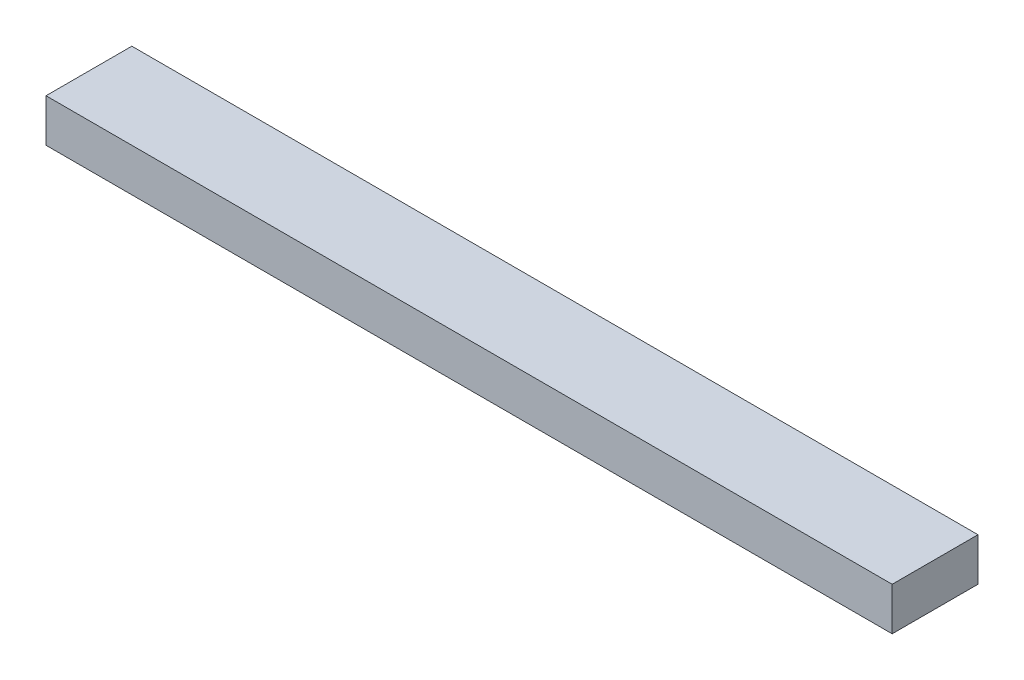
SolidWorks part; units mm, degrees
ref_plane "Front Plane" through (0, 0, 0) normal (0, 0, 1) x (1, 0, 0)
ref_plane "Top Plane" through (0, 0, 0) normal (0, 1, 0) x (1, 0, 0)
ref_plane "Right Plane" through (0, 0, 0) normal (1, 0, 0) x (0, 0, -1)
sketch "Sketch1" plane through (0, 0, 0) normal (0, 1, 0) x (1, 0, 0)
  line L1 (-25.04, 2.54) -> (25.04, 2.54)
  line L2 (-25.04, 2.54) -> (-25.04, -2.54)
  line L3 (-25.04, -2.54) -> (25.04, -2.54)
  line L4 (25.04, 2.54) -> (25.04, -2.54)
  line L5 (-25.04, 2.54) -> (25.04, -2.54) construction
  line L6 (-25.04, -2.54) -> (25.04, 2.54) construction
  point P0 (0, 0)
  dimension "D1" = 50.08
  dimension "D2" = 5.08
extrude "Boss-Extrude1" add sketch "Sketch1" along normal blind 2.54
